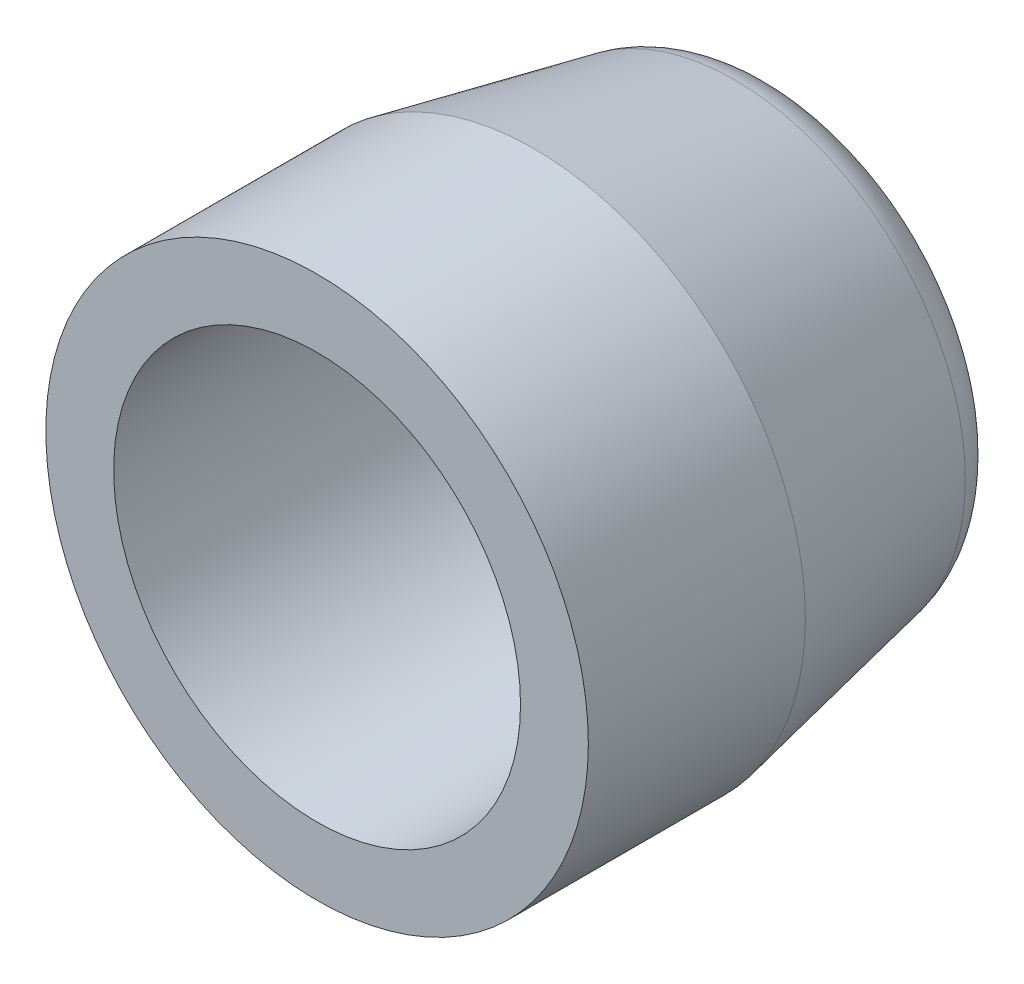
SolidWorks part; units mm, degrees
material "1060 Сплав"
ref_plane "Спереди" through (0, 0, 0) normal (0, 0, 1) x (1, 0, 0)
ref_plane "Сверху" through (0, 0, 0) normal (0, 1, 0) x (1, 0, 0)
ref_plane "Справа" through (0, 0, 0) normal (1, 0, 0) x (0, 0, -1)
sketch "Эскиз1" plane through (0, 0, 0) normal (0, 1, 0) x (1, 0, 0)
  line L0 (5, 4) -> (4.25, 7.6987)
  line L1 (0, 0) -> (5, 0)
  line L2 (0, 0) -> (0, 8.5)
  line L3 (0, 8.5) -> (5, 8.5)
  line L4 (5, 0) -> (5, 8.5)
  line L5 (0, 0) -> (3.75, 0)
  line L6 (0, 0) -> (0, 7.1)
  line L7 (0, 7.1) -> (3.75, 7.1)
  line L8 (3.75, 0) -> (3.75, 7.1)
  line L10 (0, 7.1) -> (1.5, 7.1)
  line L11 (0, 7.1) -> (0, 8.5)
  line L12 (0, 8.5) -> (1.5, 8.5)
  line L13 (1.5, 7.1) -> (1.5, 8.5)
  arc A0 (4.25, 7.6987) -> (3.2699, 8.5) centre (3.2699, 7.5) ccw
  dimension "D6" = 1
  dimension "D1" = 5
  dimension "D2" = 3.75
  dimension "D3" = 8.5
  dimension "D4" = 7.1
  dimension "D5" = 4.25
  dimension "D7" = 4
  dimension "D8" = 1.5
revolve "Повернуть1" add sketch "Эскиз1" angle 360 about L2
cosmetic thread "Условное изображение резьбы1" parameters "D2"=8
